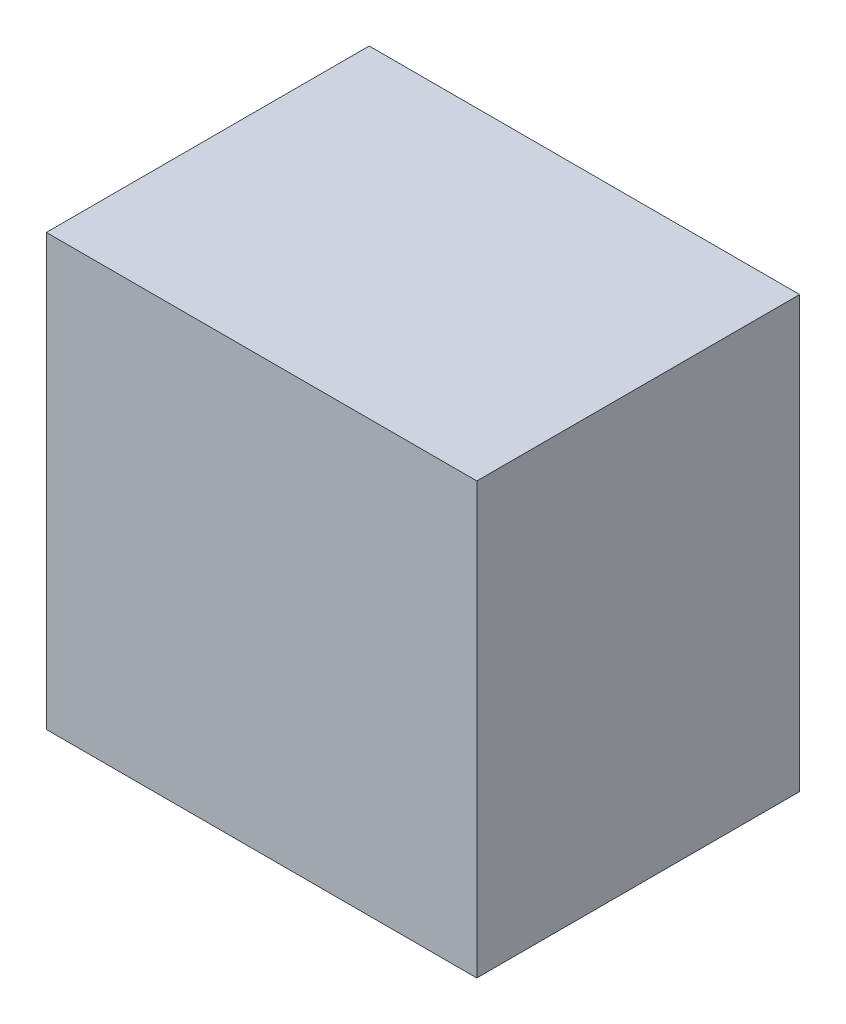
SolidWorks part; units mm, degrees
ref_plane "Front Plane" through (0, 0, 0) normal (0, 0, 1) x (1, 0, 0)
ref_plane "Top Plane" through (0, 0, 0) normal (0, 1, 0) x (1, 0, 0)
ref_plane "Right Plane" through (0, 0, 0) normal (1, 0, 0) x (0, 0, -1)
other "Configuration Table"
sketch "Sketch1" plane through (0, 0, 0) normal (0, 0, 1) x (1, 0, 0)
  line L1 (60, 200) -> (160, 200)
  line L2 (60, 200) -> (60, 300)
  line L3 (60, 300) -> (160, 300)
  line L4 (160, 200) -> (160, 300)
extrude "OVEN_pano_plc_1" add sketch "Sketch1" against normal blind 75 from offset 173 separate body
